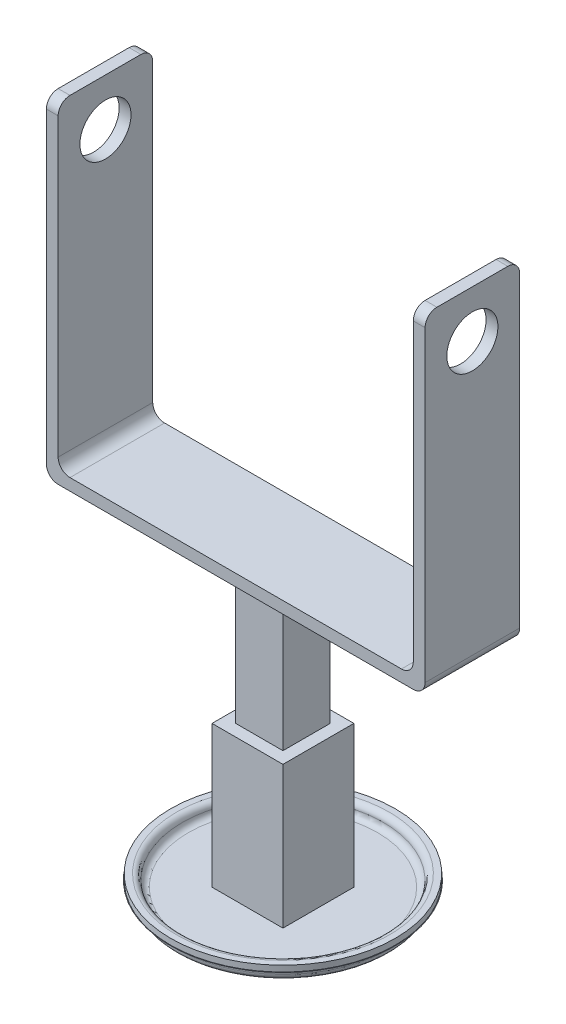
SolidWorks part; units mm, degrees
ref_plane "Front Plane" through (0, 0, 0) normal (0, 0, 1) x (1, 0, 0)
ref_plane "Top Plane" through (0, 0, 0) normal (0, 1, 0) x (1, 0, 0)
ref_plane "Right Plane" through (0, 0, 0) normal (1, 0, 0) x (0, 0, -1)
sketch "Sketch2" plane through (0, 0, 0) normal (0, 0, 1) x (1, 0, 0)
  line L0 (0, 0) -> (54.2617, 0)
  line L2 (60.6117, 6.35) -> (60.325, 6.35)
  line L3 (60.325, 6.35) -> (60.325, 9.525)
  line L4 (60.325, 9.525) -> (57.15, 9.525)
  line L6 (50.8, 3.175) -> (0, 3.175)
  line L7 (0, 3.175) -> (0, 0)
  arc A0 (53.975, 6.35) -> (50.8, 3.175) centre (50.8, 6.35) cw
  arc A1 (57.15, 9.525) -> (53.975, 6.35) centre (57.15, 6.35) ccw
  arc A2 (57.4367, 3.175) -> (60.6117, 6.35) centre (60.6117, 3.175) cw
  arc A3 (54.2617, 0) -> (57.4367, 3.175) centre (54.2617, 3.175) ccw
  point P16 (53.975, 3.175)
  dimension "D3" = 3.175
  dimension "D1" = 50.8
  dimension "D2" = 3.175
  dimension "D4" = 60.325
  dimension "D5" = 3.175
revolve "Revolve1" add sketch "Sketch2" angle 360 about L7
sketch "Sketch3" plane through (0, 3.175, 0) normal (0, 1, 0) x (1, 0, 0)
  line L1 (19.05, 19.05) -> (-19.05, 19.05)
  line L2 (19.05, 19.05) -> (19.05, -19.05)
  line L3 (19.05, -19.05) -> (-19.05, -19.05)
  line L4 (-19.05, 19.05) -> (-19.05, -19.05)
  line L5 (19.05, 19.05) -> (-19.05, -19.05) construction
  line L6 (19.05, -19.05) -> (-19.05, 19.05) construction
  point P0 (0, 0)
  dimension "D1" = 38.1
  dimension "D2" = 38.1
extrude "Boss-Extrude1" add sketch "Sketch3" along normal blind 76.2
sketch "Sketch4" plane through (0, 79.375, 0) normal (0, 1, 0) x (1, 0, 0)
  line L1 (12.7, 12.7) -> (-12.7, 12.7)
  line L2 (12.7, 12.7) -> (12.7, -12.7)
  line L3 (12.7, -12.7) -> (-12.7, -12.7)
  line L4 (-12.7, 12.7) -> (-12.7, -12.7)
  line L5 (12.7, 12.7) -> (-12.7, -12.7) construction
  line L6 (12.7, -12.7) -> (-12.7, 12.7) construction
  point P0 (0, 0)
  dimension "D1" = 25.4
  dimension "D2" = 25.4
extrude "Boss-Extrude2" add sketch "Sketch4" along normal blind 76.2
sketch "Sketch5" plane through (0, 0, 0) normal (0, 0, 1) x (1, 0, 0)
  line L0 (101.7545, 155.575) -> (-101.6995, 155.575)
  line L3 (101.7545, 155.575) -> (101.7545, 333.375)
  line L4 (-101.6995, 155.575) -> (-101.6995, 333.375)
  line L5 (-101.6995, 333.375) -> (-95.3495, 333.375)
  line L6 (-95.3495, 333.375) -> (-95.3495, 161.925)
  line L7 (-95.3495, 161.925) -> (95.4045, 161.925)
  line L8 (95.4045, 161.925) -> (95.4045, 333.375)
  line L9 (95.4045, 333.375) -> (101.7545, 333.375)
  point P3 (0, 155.575)
  point P4 (0.0275, 155.575)
  point P6 (-98.5245, 333.375)
  dimension "D1" = 203.454
  dimension "D2" = 6.35
  dimension "D3" = 6.35
  dimension "D4" = 6.35
  dimension "D5" = 177.8
extrude "Boss-Extrude3" add sketch "Sketch5" along normal mid plane 50.8
fillet "Fillet1" radius 6.35 1 edges at (95.4045, 161.925, 0)
fillet "Fillet2" radius 6.35 1 edges at (-95.3495, 161.925, 0)
fillet "Fillet3" radius 6.35 2 edges at (-101.6995, 155.575, 0) (101.7545, 155.575, 0)
fillet "Fillet4" radius 6.35 4 edges at (-98.5245, 333.375, -25.4) (-98.5245, 333.375, 25.4) (98.5795, 333.375, 25.4) (98.5795, 333.375, -25.4)
sketch "Sketch6" plane through (101.7545, 0, 0) normal (1, 0, 0) x (0, 0, -1)
  line L0 (0, 333.375) -> (0, 161.925) construction
  line L1 (-19.05, 333.375) -> (19.05, 333.375) construction
  line L2 (-25.4, 161.925) -> (25.4, 161.925) construction
  line L3 (-87.8855, 307.975) -> (163.148, 307.975) construction
  circle A0 centre (0, 307.975) radius 13.716
  dimension "D2" = 27.432
  dimension "D1" = 25.4
extrude "Cut-Extrude1" cut sketch "Sketch6" against normal through all
